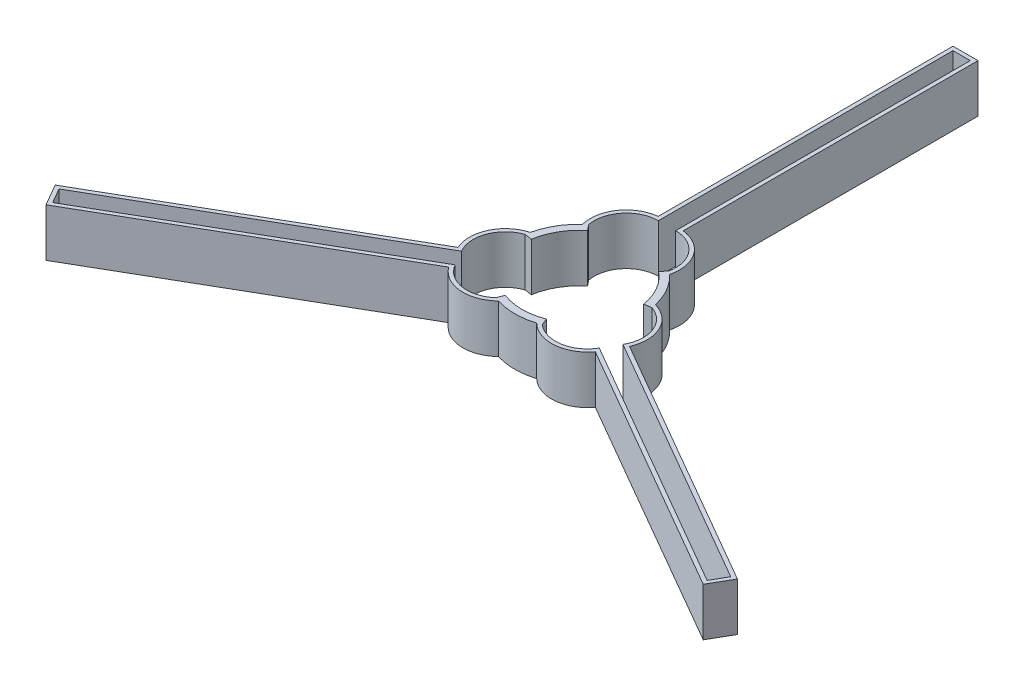
SolidWorks part; units mm, degrees
ref_plane "Front Plane" through (0, 0, 0) normal (0, 0, 1) x (1, 0, 0)
ref_plane "Top Plane" through (0, 0, 0) normal (0, 1, 0) x (1, 0, 0)
ref_plane "Right Plane" through (0, 0, 0) normal (1, 0, 0) x (0, 0, -1)
sketch "Sketch1" plane through (0, 0, 0) normal (0, 1, 0) x (1, 0, 0)
  line L0 (0, 133.3841) -> (0, -45.2268) construction
  line L1 (-53.2552, 0) -> (46.6987, 0) construction
  line L2 (25.1595, -11.4082) -> (104.6668, -57.3117)
  line L3 (104.6668, -57.3117) -> (101.9668, -61.9883)
  line L4 (-2.7, 27.4929) -> (-2.7, 119.3)
  line L5 (-2.7, 119.3) -> (2.7, 119.3)
  line L6 (-2.7, 79.0085) -> (-2.7, 10.6726) construction
  line L7 (-3.9, 120.5) -> (-3.9, 28.6284)
  line L8 (-3.9, 120.5) -> (0, 120.5)
  line L9 (-12.5187, 15.5975) -> (0, 0) construction
  line L10 (106.3061, -56.8725) -> (26.7429, -10.9367)
  line L11 (106.3061, -56.8725) -> (104.3561, -60.25)
  line L12 (19.7672, 3.0428) -> (17.494, 2.6929)
  line L13 (7.2484, -18.6403) -> (6.4149, -16.4966)
  line L14 (22.4595, -16.0847) -> (101.9668, -61.9883)
  line L15 (102.4061, -63.6275) -> (22.8429, -17.6917)
  line L16 (102.4061, -63.6275) -> (104.3561, -60.25)
  line L17 (115.514, -66.692) -> (-39.1675, 22.6134) construction
  line L18 (26.6276, 46.1204) -> (-23.3493, -40.4422) construction
  line L19 (69.7734, -37.166) -> (10.5927, -2.998) construction
  line L20 (19.7672, 3.0428) -> (0, 0) construction
  line L21 (-22.4595, -16.0847) -> (-101.9668, -61.9883)
  line L22 (-101.9668, -61.9883) -> (-104.6668, -57.3117)
  line L23 (-102.4061, -63.6275) -> (-22.8429, -17.6917)
  line L24 (-12.5187, 15.5975) -> (-11.0791, 13.8038)
  line L25 (12.5187, 15.5975) -> (11.0791, 13.8038)
  line L26 (2.7, 27.4929) -> (2.7, 119.3)
  line L27 (3.9, 120.5) -> (3.9, 28.6284)
  line L28 (3.9, 120.5) -> (0, 120.5)
  line L29 (-102.4061, -63.6275) -> (-104.3561, -60.25)
  line L30 (-7.2484, -18.6403) -> (-6.4149, -16.4966)
  line L31 (-19.7672, 3.0428) -> (-17.494, 2.6929)
  line L32 (-25.1595, -11.4082) -> (-104.6668, -57.3117)
  line L33 (-106.3061, -56.8725) -> (-26.7429, -10.9367)
  line L34 (-106.3061, -56.8725) -> (-104.3561, -60.25)
  line L35 (-115.514, -66.692) -> (39.1675, 22.6134) construction
  line L36 (26.6276, -46.1204) -> (-23.3493, 40.4422) construction
  line L37 (-67.0734, -41.8425) -> (-7.8927, -7.6746) construction
  line L38 (-7.2484, -18.6403) -> (0, 0) construction
  circle A0 centre (0, 0) radius 17.7
  circle A1 centre (0, 0) radius 20
  arc A2 (-2.7, 27.4929) -> (-12.5187, 15.5975) centre (-2.7, 17.4929) ccw
  arc A3 (-3.9, 28.6284) -> (-13.5491, 14.7113) centre (-2.7, 17.4929) ccw
  arc A4 (3.9, 28.6284) -> (13.5491, 14.7113) centre (2.7, 17.4929) cw
  arc A5 (2.7, 27.4929) -> (12.5187, 15.5975) centre (2.7, 17.4929) cw
  arc A6 (25.1595, -11.4082) -> (19.7672, 3.0428) centre (16.4993, -6.4082) ccw
  arc A7 (26.7429, -10.9367) -> (19.5149, 4.3782) centre (16.4993, -6.4082) ccw
  arc A8 (22.8429, -17.6917) -> (5.9658, -19.0895) centre (13.7993, -11.0847) cw
  arc A9 (22.4595, -16.0847) -> (7.2484, -18.6403) centre (13.7993, -11.0847) cw
  arc A10 (-22.4595, -16.0847) -> (-7.2484, -18.6403) centre (-13.7993, -11.0847) ccw
  arc A11 (-22.8429, -17.6917) -> (-5.9658, -19.0895) centre (-13.7993, -11.0847) ccw
  arc A12 (-26.7429, -10.9367) -> (-19.5149, 4.3782) centre (-16.4993, -6.4082) cw
  arc A13 (-25.1595, -11.4082) -> (-19.7672, 3.0428) centre (-16.4993, -6.4082) cw
  point P16 (-1.95, 120.5)
  point P19 (0, 20)
  point P30 (17.3205, -10)
  point P34 (0, 0)
  point P43 (0, 0)
  point P56 (0, 119.3)
  point P58 (103.3168, -59.65)
  point P69 (-17.3205, -10)
  point P73 (0, 0)
  point P84 (-103.3168, -59.65)
  point P85 (0, 0)
  dimension "D1" = 35.4
  dimension "D2" = 40
  dimension "D6" = 10
  dimension "D8" = 1.2
  dimension "D3" = 3
  dimension "D5" = 2.7
  dimension "D7" = 1.2
  dimension "D9" = 1.2
  dimension "D10" = 99.3
extrude "Boss-Extrude1" add sketch "Sketch1" along normal blind 15 contours L26 A5 A1 A4 L27 L28 L8 L7 A3 A2 L4 L5 | L24 A1 L31 A0 | L32 A13 A1 A12 L33 L34 L29 L23 A11 A10 L21 L22 | L12 A1 L25 A0 | L30 A1 L13 A0 | L14 A9 A1 A8 L15 L16 L11 L10 A7 A6 L2 L3
